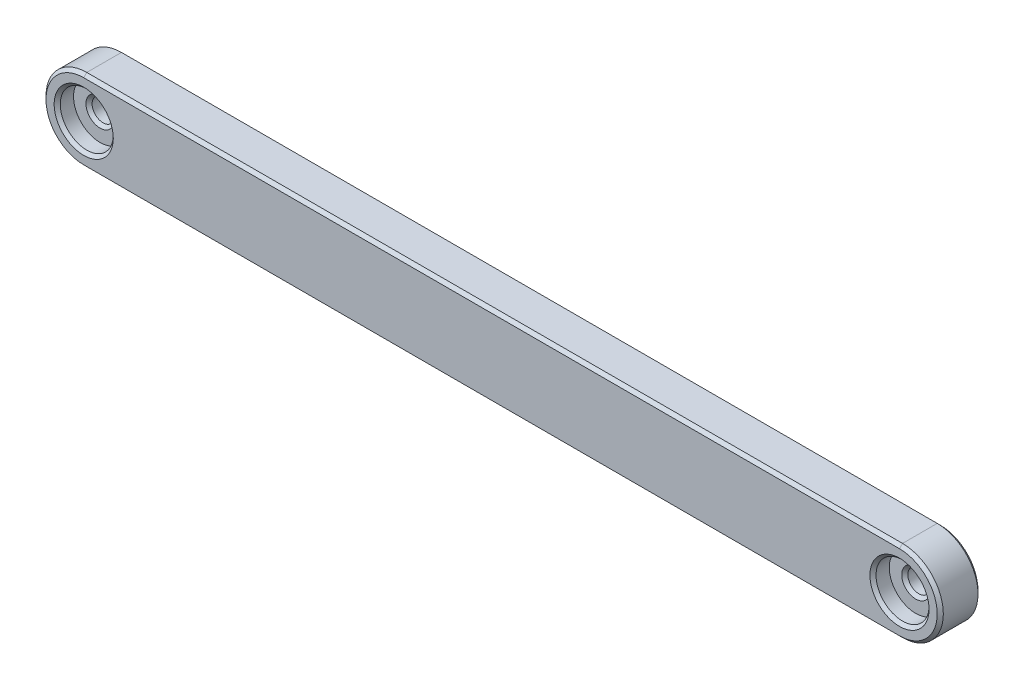
SolidWorks part; units mm, degrees
ref_plane "Front Plane" through (0, 0, 0) normal (0, 0, 1) x (1, 0, 0)
ref_plane "Top Plane" through (0, 0, 0) normal (0, 1, 0) x (1, 0, 0)
ref_plane "Right Plane" through (0, 0, 0) normal (1, 0, 0) x (0, 0, -1)
sketch "Sketch1" plane through (0, 0, 0) normal (0, 0, 1) x (1, 0, 0)
  line L0 (-100, 10) -> (100, 10)
  line L1 (-100, 10) -> (100, -10) construction
  line L2 (100, -10) -> (-100, -10)
  arc A0 (-100, 10) -> (-100, -10) centre (-100, 0) ccw
  arc A2 (100, 10) -> (100, -10) centre (100, 0) cw
  circle A4 centre (100, 0) radius 2.7
  circle A5 centre (-100, 0) radius 2.7
  dimension "D3" = 5.4
  dimension "D1" = 200
  dimension "D2" = 20
extrude "Boss-Extrude1" add sketch "Sketch1" along normal blind 10
sketch "Sketch2" plane through (0, 0, 10) normal (0, 0, 1) x (1, 0, 0)
  circle A0 centre (-100, 0) radius 6.5
  circle A1 centre (100, 0) radius 6.5
  dimension "D1" = 13
extrude "Cut-Extrude1" cut sketch "Sketch2" against normal blind 4
chamfer "Chamfer1" distance 0.75 angle 45 14 edges at (0, -10, 10) (-110, 0, 10) (110, 0, 10) (0, 10, 10) (0, -10, 0) (-110, 0, 0) (110, 0, 0) (0, 10, 0) (-97.3, 0, 0) (102.7, 0, 0) (-97.3, 0, 6) (102.7, 0, 6) (106.5, 0, 10) (-93.5, 0, 10)
